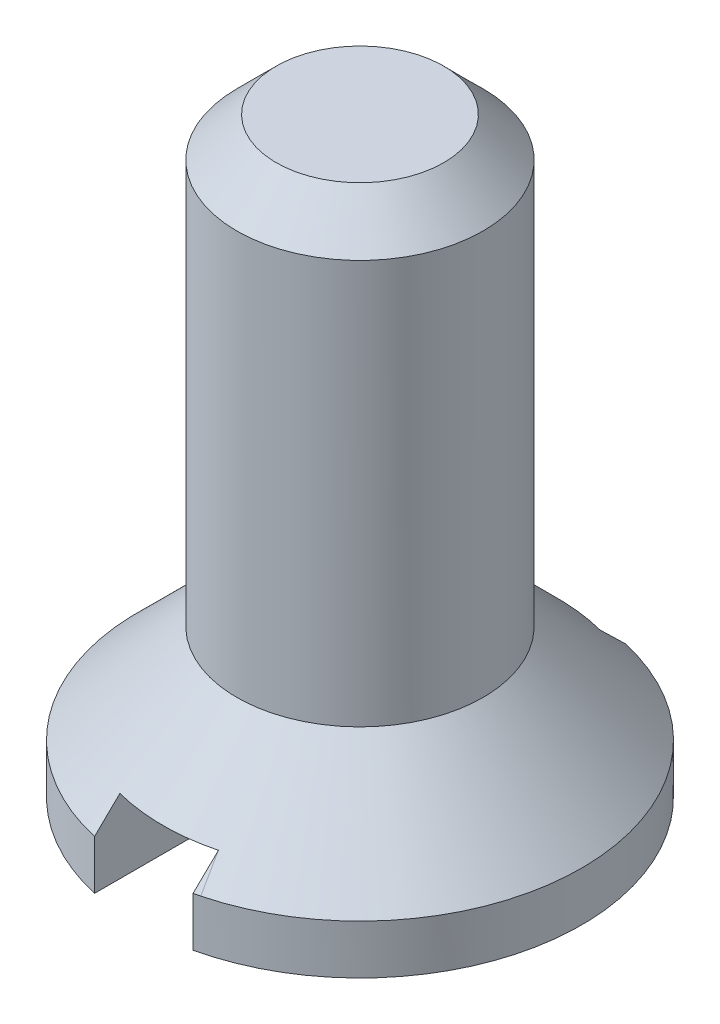
SolidWorks part; units mm, degrees
ref_plane "Спереди" through (0, 0, 0) normal (0, 0, 1) x (1, 0, 0)
ref_plane "Сверху" through (0, 0, 0) normal (0, 1, 0) x (1, 0, 0)
ref_plane "Справа" through (0, 0, 0) normal (1, 0, 0) x (0, 0, -1)
sketch "Эскиз1" plane through (0, 0, 0) normal (0, 0, 1) x (1, 0, 0)
  line L0 (0, 0) -> (-2.25, 0)
  line L1 (-2.25, 0) -> (-2.25, 0.5)
  line L2 (-2.25, 0.5) -> (-1.25, 1.5)
  line L3 (-1.25, 1.5) -> (-1.25, 6)
  line L4 (-1.25, 6) -> (0, 6)
  line L5 (0, 6) -> (0, 0)
  line L6 (-1.25, 1.5) -> (0, 1.5) construction
  dimension "D1" = 6
  dimension "D2" = 2.25
  dimension "D3" = 1.25
  dimension "D4" = 45
  dimension "D5" = 1.5
revolve "Повернуть1" add sketch "Эскиз1" angle 360 about L5
sketch "Эскиз2" plane through (0, 0, 0) normal (0, 0, 1) x (1, 0, 0)
  line L0 (-2.25, 0) -> (2.25, 0) construction
  line L1 (-0.5, 0) -> (0.5, 0)
  line L2 (-0.5, 0) -> (-0.5, 0.75)
  line L3 (-0.5, 0.75) -> (0.5, 0.75)
  line L4 (0.5, 0) -> (0.5, 0.75)
  dimension "D1" = 0.75
  dimension "D2" = 1
extrude "Вырез-Вытянуть1" cut sketch "Эскиз2" against normal mid plane 20
chamfer "Фаска1" distance 0.4 angle 45 1 edges at (-1.25, 6, 0)
